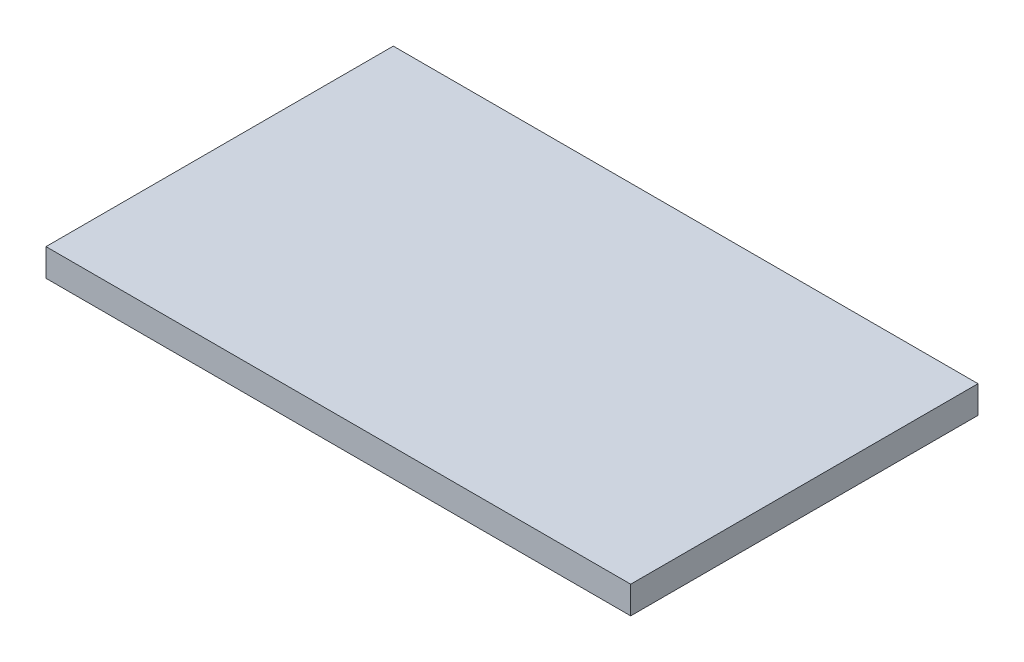
SolidWorks part; units mm, degrees
ref_plane "Front Plane" through (0, 0, 0) normal (0, 0, 1) x (1, 0, 0)
ref_plane "Top Plane" through (0, 0, 0) normal (0, 1, 0) x (1, 0, 0)
ref_plane "Right Plane" through (0, 0, 0) normal (1, 0, 0) x (0, 0, -1)
other "Configuration Table"
sketch "Sketch1" plane through (0, 0, 0) normal (0, 0, 1) x (1, 0, 0)
  line L1 (61.5, 121.5) -> (1338.5, 121.5)
  line L2 (61.5, 121.5) -> (61.5, 181.5)
  line L3 (61.5, 181.5) -> (1338.5, 181.5)
  line L4 (1338.5, 121.5) -> (1338.5, 181.5)
extrude "STORE_pu_alt_1" add sketch "Sketch1" against normal blind 758.5 separate body
